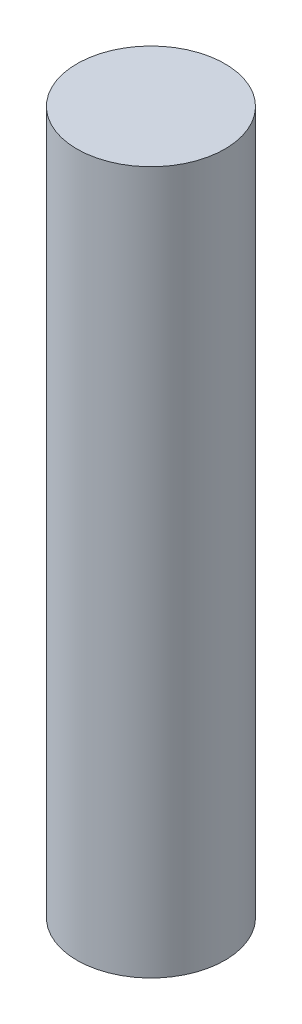
SolidWorks part; units mm, degrees
ref_plane "Front Plane" through (0, 0, 0) normal (0, 0, 1) x (1, 0, 0)
ref_plane "Top Plane" through (0, 0, 0) normal (0, 1, 0) x (1, 0, 0)
ref_plane "Right Plane" through (0, 0, 0) normal (1, 0, 0) x (0, 0, -1)
sketch "Sketch1" plane through (0, 0, 0) normal (0, 1, 0) x (1, 0, 0)
  circle A0 centre (0, 0) radius 4
  dimension "D1" = 8
extrude "Boss-Extrude1" add sketch "Sketch1" along normal blind 38
